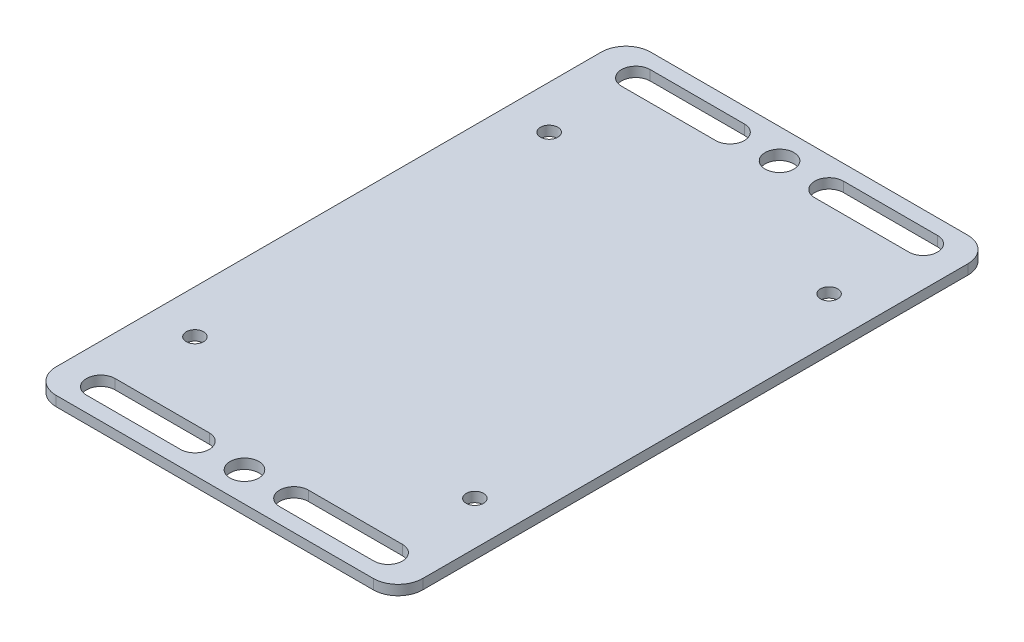
SolidWorks part; units mm, degrees
ref_plane "Front Plane" through (0, 0, 0) normal (0, 0, 1) x (1, 0, 0)
ref_plane "Top Plane" through (0, 0, 0) normal (0, 1, 0) x (1, 0, 0)
ref_plane "Right Plane" through (0, 0, 0) normal (1, 0, 0) x (0, 0, -1)
sketch "Sketch1" plane through (0, 0, 0) normal (0, 1, 0) x (1, 0, 0)
  line L0 (37, 54) -> (-37, 54) construction
  line L1 (-33, -40.65) -> (33, -40.65) construction
  line L2 (-33, -40.65) -> (-33, 40.65) construction
  line L3 (-33, 40.65) -> (33, 40.65) construction
  line L4 (33, -40.65) -> (33, 40.65) construction
  line L5 (-33, -40.65) -> (33, 40.65) construction
  line L6 (-33, 40.65) -> (33, -40.65) construction
  line L7 (-37, 60) -> (37, 60)
  line L8 (-37, 60) -> (-37, -60)
  line L9 (-37, -60) -> (37, -60)
  line L10 (37, 60) -> (37, -60)
  line L11 (-37, 60) -> (37, -60) construction
  line L12 (-37, -60) -> (37, 60) construction
  point P0 (0, 0)
  point P7 (0, 0)
  dimension "D1" = 66
  dimension "D2" = 81.3
  dimension "D3" = 74
  dimension "D4" = 120
  dimension "D5" = 6
extrude "Boss-Extrude1" add sketch "Sketch1" along normal blind 2
sketch "Sketch3" plane through (0, 2, 0) normal (0, 1, 0) x (1, 0, 0)
  line L0 (-37, 54) -> (37, 54) construction
  line L1 (-37, 60) -> (-37, -60) construction
  line L2 (37, 60) -> (37, -60) construction
  line L3 (-37, 60) -> (37, 60) construction
  line L4 (-29, 54) -> (-10, 54) construction
  line L5 (-29, 56.9) -> (-10, 56.9)
  line L6 (-29, 51.1) -> (-10, 51.1)
  line L7 (-37, 60) -> (-37, -60) construction
  line L8 (10, 54) -> (29, 54) construction
  line L9 (10, 56.9) -> (29, 56.9)
  line L10 (10, 51.1) -> (29, 51.1)
  arc A0 (-29, 56.9) -> (-29, 51.1) centre (-29, 54) ccw
  arc A1 (-10, 51.1) -> (-10, 56.9) centre (-10, 54) ccw
  circle A2 centre (0, 54) radius 2.9
  arc A3 (10, 56.9) -> (10, 51.1) centre (10, 54) ccw
  arc A4 (29, 51.1) -> (29, 56.9) centre (29, 54) ccw
  point P10 (-19.5, 54)
  point P21 (19.5, 54)
  dimension "D2" = 5.8
  dimension "D1" = 6
  dimension "D3" = 8
  dimension "D4" = 10
  dimension "D5" = 10
  dimension "D6" = 8
extrude "Cut-Extrude1" cut sketch "Sketch3" against normal through all
mirror "Mirror1" about plane through (0, 0, 0) normal (0, 0, 1) of "Cut-Extrude1"
fillet "Fillet1" radius 5 4 edges at (-37, 1, 60) (37, 1, 60) (37, 1, -60) (-37, 1, -60)
sketch "Sketch5" plane through (0, 2, 0) normal (0, 1, 0) x (1, 0, 0)
  line L1 (-28.25, -35.75) -> (28.25, -35.75) construction
  line L2 (-28.25, -35.75) -> (-28.25, 35.75) construction
  line L3 (-28.25, 35.75) -> (28.25, 35.75) construction
  line L4 (28.25, -35.75) -> (28.25, 35.75) construction
  line L5 (-28.25, -35.75) -> (28.25, 35.75) construction
  line L6 (-28.25, 35.75) -> (28.25, -35.75) construction
  circle A0 centre (-28.25, 35.75) radius 1.75
  circle A1 centre (28.25, 35.75) radius 1.75
  circle A2 centre (-28.25, -35.75) radius 1.75
  circle A3 centre (28.25, -35.75) radius 1.75
  point P0 (0, 0)
  dimension "D3" = 3.5
  dimension "D1" = 71.5
  dimension "D2" = 56.5
extrude "Cut-Extrude2" cut sketch "Sketch5" against normal through all
